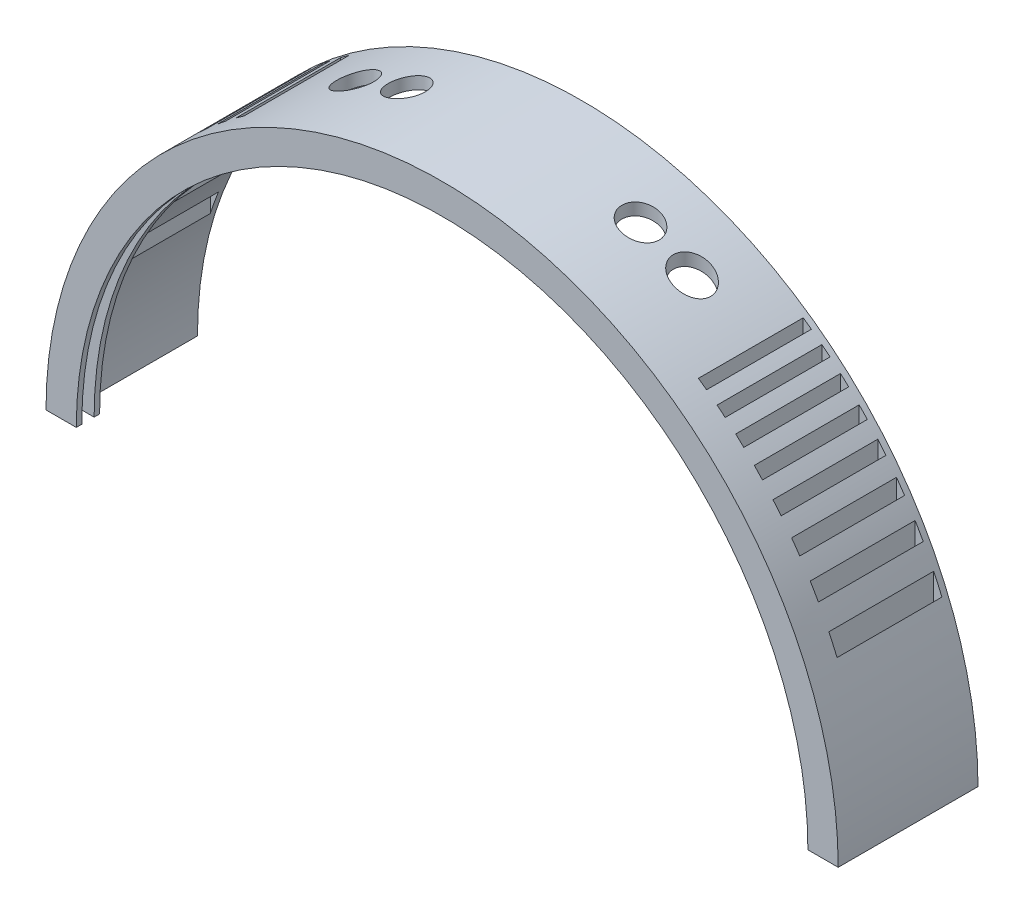
SolidWorks part; units mm, degrees
material "ABS"
ref_plane "Plan de face" through (0, 0, 0) normal (0, 0, 1) x (1, 0, 0)
ref_plane "Plan de dessus" through (0, 0, 0) normal (0, 1, 0) x (1, 0, 0)
ref_plane "Plan de droite" through (0, 0, 0) normal (1, 0, 0) x (0, 0, -1)
sketch "Esquisse1" plane through (0, 0, 0) normal (0, 0, 1) x (1, 0, 0)
  line L2 (-335, 205) -> (-330, 205)
  line L3 (0, 205) -> (5, 205)
  arc A0 (0, 205) -> (-330, 205) centre (-165, 205) ccw
  arc A2 (5, 205) -> (-335, 205) centre (-165, 205) ccw
  dimension "D2" = 5
extrude "Boss.-Extru.1" add sketch "Esquisse1" along normal blind 50
sketch "Esquisse2" plane through (0, 205, 0) normal (0, -1, 0) x (1, 0, 0)
  line L0 (0, 0) -> (-330, 0) construction
  line L1 (0, 0) -> (0, 2.5) construction
  line L2 (0, 50) -> (0, 0) construction
  line L3 (0, 2.5) -> (-330, 2.5) construction
  line L4 (-330, 50) -> (-330, 0) construction
  line L5 (-330, 2.5) -> (-330, 0) construction
  line L6 (-330, 50) -> (0, 50) construction
  line L7 (0, 50) -> (0, 47.5) construction
  line L8 (0, 47.5) -> (-330, 47.5) construction
  line L9 (-330, 47.5) -> (-330, 50) construction
  line L10 (-322, 2.5) -> (-322, 47.5) construction
  line L11 (-322, 2.5) -> (-322, 47.5)
  line L12 (-322, 47.5) -> (-318.5, 47.5)
  line L13 (-318.5, 47.5) -> (-318.5, 2.5)
  line L14 (-318.5, 2.5) -> (-322, 2.5)
  line L15 (-310.5, 2.5) -> (-314, 2.5)
  line L16 (-314, 2.5) -> (-314, 47.5)
  line L17 (-314, 47.5) -> (-310.5, 47.5)
  line L18 (-310.5, 47.5) -> (-310.5, 2.5)
  line L19 (-302.5, 2.5) -> (-306, 2.5)
  line L20 (-306, 2.5) -> (-306, 47.5)
  line L21 (-306, 47.5) -> (-302.5, 47.5)
  line L22 (-302.5, 47.5) -> (-302.5, 2.5)
  line L23 (-294.5, 2.5) -> (-298, 2.5)
  line L24 (-298, 2.5) -> (-298, 47.5)
  line L25 (-298, 47.5) -> (-294.5, 47.5)
  line L26 (-294.5, 47.5) -> (-294.5, 2.5)
  line L27 (-286.5, 2.5) -> (-290, 2.5)
  line L28 (-290, 2.5) -> (-290, 47.5)
  line L29 (-290, 47.5) -> (-286.5, 47.5)
  line L30 (-286.5, 47.5) -> (-286.5, 2.5)
  line L31 (-278.5, 2.5) -> (-282, 2.5)
  line L32 (-282, 2.5) -> (-282, 47.5)
  line L33 (-282, 47.5) -> (-278.5, 47.5)
  line L34 (-278.5, 47.5) -> (-278.5, 2.5)
  line L35 (-270.5, 2.5) -> (-274, 2.5)
  line L36 (-274, 2.5) -> (-274, 47.5)
  line L37 (-274, 47.5) -> (-270.5, 47.5)
  line L38 (-270.5, 47.5) -> (-270.5, 2.5)
  line L39 (-262.5, 2.5) -> (-266, 2.5)
  line L40 (-266, 2.5) -> (-266, 47.5)
  line L41 (-266, 47.5) -> (-262.5, 47.5)
  line L42 (-262.5, 47.5) -> (-262.5, 2.5)
  line L43 (-322, 27.0183) -> (-330, 27.0183) construction
  line L44 (-8, 47.5) -> (-8, 2.5) construction
  line L45 (-8, 2.5) -> (-8, 47.5)
  line L46 (-8, 47.5) -> (-11.5, 47.5)
  line L47 (-11.5, 47.5) -> (-11.5, 2.5)
  line L48 (-11.5, 2.5) -> (-8, 2.5)
  line L49 (-19.5, 2.5) -> (-16, 2.5)
  line L50 (-16, 2.5) -> (-16, 47.5)
  line L51 (-16, 47.5) -> (-19.5, 47.5)
  line L52 (-19.5, 47.5) -> (-19.5, 2.5)
  line L53 (-27.5, 2.5) -> (-24, 2.5)
  line L54 (-24, 2.5) -> (-24, 47.5)
  line L55 (-24, 47.5) -> (-27.5, 47.5)
  line L56 (-27.5, 47.5) -> (-27.5, 2.5)
  line L57 (-35.5, 2.5) -> (-32, 2.5)
  line L58 (-32, 2.5) -> (-32, 47.5)
  line L59 (-32, 47.5) -> (-35.5, 47.5)
  line L60 (-35.5, 47.5) -> (-35.5, 2.5)
  line L61 (-43.5, 2.5) -> (-40, 2.5)
  line L62 (-40, 2.5) -> (-40, 47.5)
  line L63 (-40, 47.5) -> (-43.5, 47.5)
  line L64 (-43.5, 47.5) -> (-43.5, 2.5)
  line L65 (-51.5, 2.5) -> (-48, 2.5)
  line L66 (-48, 2.5) -> (-48, 47.5)
  line L67 (-48, 47.5) -> (-51.5, 47.5)
  line L68 (-51.5, 47.5) -> (-51.5, 2.5)
  line L69 (-59.5, 2.5) -> (-56, 2.5)
  line L70 (-56, 2.5) -> (-56, 47.5)
  line L71 (-56, 47.5) -> (-59.5, 47.5)
  line L72 (-59.5, 47.5) -> (-59.5, 2.5)
  line L73 (-67.5, 2.5) -> (-64, 2.5)
  line L74 (-64, 2.5) -> (-64, 47.5)
  line L75 (-64, 47.5) -> (-67.5, 47.5)
  line L76 (-67.5, 47.5) -> (-67.5, 2.5)
  dimension "D1" = 2.5
  dimension "D2" = 2.5
  dimension "D3" = 8
  dimension "D4" = 3.5
  dimension "D5" = 3.5
  dimension "D7" = 8
  dimension "D8" = 3.5
  dimension "D10" = 4.5
  dimension "D6" = 8
  dimension "D9" = 8
extrude "Enlèv. mat.-Extru.1" cut sketch "Esquisse2" against normal blind 1500
sketch "Esquisse3" plane through (0, 205, 0) normal (0, -1, 0) x (1, 0, 0)
  line L0 (0, 0) -> (-72.0387, 0) construction
  line L1 (-325, 0) -> (-5, 0) construction
  line L2 (-72.0387, 0) -> (-72.0387, 50) construction
  line L3 (-5, 50) -> (-325, 50) construction
  line L4 (-72.0387, 50) -> (0, 50) construction
  line L5 (0, 50) -> (0, 0) construction
  line L6 (-64, 2.5) -> (-64, 0) construction
  line L7 (-64, 47.5) -> (-64, 50) construction
  line L8 (-64, 47.5) -> (-104.2959, 47.5) construction
  line L9 (-104.2959, 47.5) -> (-104.2959, 2.5) construction
  line L10 (-104.2959, 2.5) -> (-64, 2.5) construction
  line L12 (-78.9167, 37.75) -> (-78.9167, 50) construction
  line L13 (-78.9167, 12.25) -> (-78.9167, 0) construction
  line L17 (0, 50) -> (-330, 50) construction
  line L18 (-165, 50) -> (-165, 0) construction
  line L23 (-78.9167, 25) -> (-92.7167, 25) construction
  line L24 (-129.0667, 25) -> (-114.8367, 25) construction
  line L25 (-129.0667, 37.75) -> (-78.9167, 37.75) construction
  line L26 (-78.9167, 37.75) -> (-78.9167, 12.25) construction
  line L27 (-129.0667, 12.25) -> (-78.9167, 12.25) construction
  line L28 (-129.0667, 12.25) -> (-129.0667, 37.75) construction
  circle A0 centre (-92.7167, 25) radius 8
  circle A1 centre (-114.8367, 25) radius 8
  circle A2 centre (-237.2833, 25) radius 8
  circle A3 centre (-215.1633, 25) radius 8
  dimension "D6" = 16
  dimension "D8" = 16
  dimension "D1" = 25.5
  dimension "D2" = 12.25
  dimension "D3" = 12.25
  dimension "D4" = 50.15
  dimension "D5" = 13.8
  dimension "D7" = 14.23
extrude "Enlèv. mat.-Extru.3" cut sketch "Esquisse3" against normal blind 1500
sketch "Esquisse4" plane through (0, 0, 50) normal (0, 0, 1) x (1, 0, 0)
  line L2 (0, 205) -> (5, 205)
  line L3 (-335, 205) -> (-330, 205)
  line L4 (-335, 205) -> (-330, 205) construction
  line L5 (0, 205) -> (5, 205) construction
  arc A6 (0, 205) -> (-165, 370) centre (-165, 205) ccw
  arc A7 (0, 205) -> (-330, 205) centre (-165, 205) ccw construction
  arc A8 (5, 205) -> (-165, 375) centre (-165, 205) ccw
  arc A9 (5, 205) -> (-335, 205) centre (-165, 205) ccw construction
  arc A10 (-330, 205) -> (-165, 370) centre (-165, 205) cw
  arc A11 (-165, 375) -> (-335, 205) centre (-165, 205) ccw
  arc A12 (0, 205) -> (-330, 205) centre (-165, 205) ccw construction
  arc A13 (5, 205) -> (-335, 205) centre (-165, 205) ccw construction
  dimension "D1" = 5
extrude "Boss.-Extru.2" add sketch "Esquisse4" along normal blind 10
sketch "Esquisse5" plane through (0, 205, 0) normal (0, -1, 0) x (-1, 0, 0)
  line L0 (5, -60) -> (0, -60)
  line L1 (0, -60) -> (0, -57.65)
  line L2 (0, -60) -> (0, 0) construction
  line L3 (0, -57.65) -> (330, -57.65)
  line L4 (330, -60) -> (330, 0) construction
  line L5 (330, -57.65) -> (330, -60)
  line L6 (330, -60) -> (0, -60)
  line L7 (0, -50) -> (0, -52.35)
  line L8 (5, -50) -> (0, -50) construction
  line L9 (0, -52.35) -> (330, -52.35)
  line L10 (330, -52.35) -> (330, -50)
  line L11 (330, -50) -> (325, -50) construction
  line L12 (330, -50) -> (0, -50)
  dimension "D1" = 2.35
  dimension "D2" = 5.3
  dimension "D3" = 2.35
extrude "Boss.-Extru.4" add sketch "Esquisse5" against normal up to next contours L9 L10 L12 L7 | L1 L3 L5 L6
sketch "Esquisse8" plane through (0, 0, 60) normal (0, 0, 1) x (1, 0, 0)
  line L0 (-330, 205) -> (-322, 205) construction
  line L1 (-335, 205) -> (5, 205) construction
  circle A0 centre (-165, 205) radius 157
  dimension "D1" = 8
extrude "Enlèv. mat.-Extru.4" cut sketch "Esquisse8" against normal blind 94
